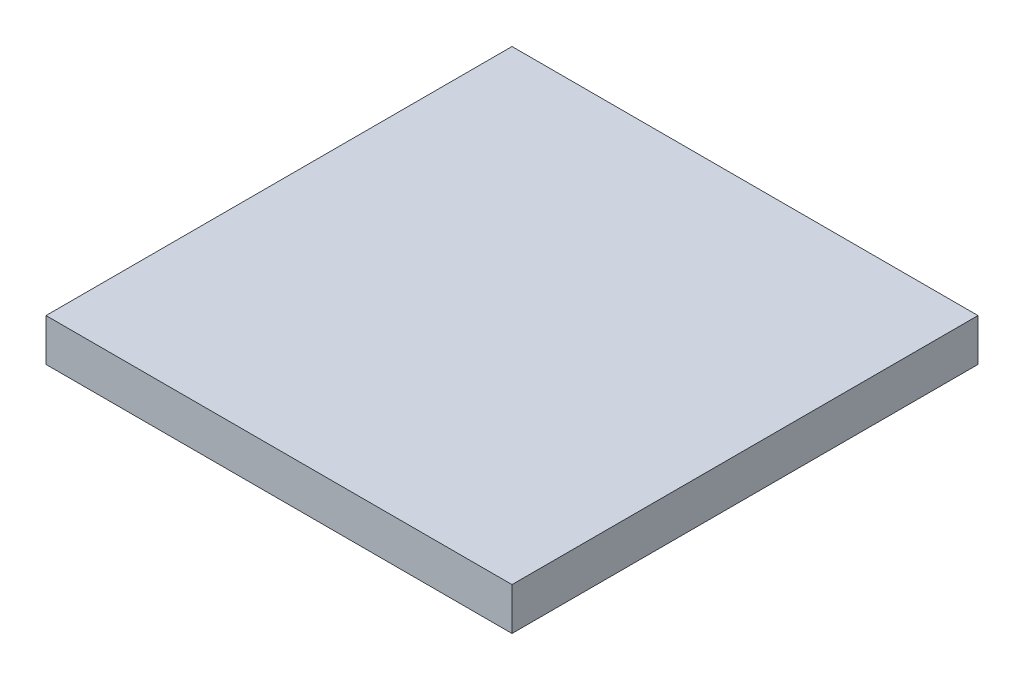
SolidWorks part; units mm, degrees
ref_plane "Front Plane" through (0, 0, 0) normal (0, 0, 1) x (1, 0, 0)
ref_plane "Top Plane" through (0, 0, 0) normal (0, 1, 0) x (1, 0, 0)
ref_plane "Right Plane" through (0, 0, 0) normal (1, 0, 0) x (0, 0, -1)
sketch "Sketch1" plane through (0, 0, 0) normal (0, 1, 0) x (1, 0, 0)
  line L1 (-11, 11) -> (11, 11)
  line L2 (-11, 11) -> (-11, -11)
  line L3 (-11, -11) -> (11, -11)
  line L4 (11, 11) -> (11, -11)
  line L5 (-11, 11) -> (11, -11) construction
  line L6 (-11, -11) -> (11, 11) construction
  point P0 (0, 0)
  dimension "D1" = 22
extrude "Boss-Extrude1" add sketch "Sketch1" along normal mid plane 2
sketch "Sketch2" plane through (0, -1, 0) normal (0, -1, 0) x (1, 0, 0)
  line L1 (8.75, -8.75) -> (0, -8.75) construction
  line L2 (8.75, -8.75) -> (8.75, 8.75) construction
  line L4 (-8.75, -8.75) -> (-8.75, 8.75) construction
  line L5 (8.75, -8.75) -> (-8.75, 8.75) construction
  line L6 (8.75, 8.75) -> (-8.75, -8.75) construction
  line L7 (0, -7.5784) -> (7.25, -7.5784) construction
  line L8 (-7.5784, -7.5784) -> (-7.5784, 7.9216) construction
  line L10 (7.25, -7.5784) -> (7.25, 7.25) construction
  line L11 (-7.5784, -7.5784) -> (7.25, 7.25) construction
  line L12 (-7.5784, 7.9216) -> (7.25, -7.5784) construction
  line L13 (0, 11.6827) -> (0, -12.9744) construction
  line L15 (-7.25, 7.25) -> (-7.25, 8.75)
  line L16 (-8.75, -8.75) -> (8.75, -8.75)
  line L17 (-8.75, -8.75) -> (-8.75, 8.75)
  line L18 (-8.75, 8.75) -> (-7.25, 8.75)
  line L19 (0, -8.75) -> (-8.75, -8.75) construction
  line L20 (-7.5784, -7.5784) -> (0, -7.5784) construction
  line L21 (-6.8004, 0) -> (6.0801, 0) construction
  line L26 (8.75, -8.75) -> (8.75, 8.75)
  line L27 (-8.75, -8.75) -> (8.75, 8.75) construction
  line L28 (-8.75, 8.75) -> (8.75, -8.75) construction
  line L29 (-7.25, -7.25) -> (7.25, -7.25)
  line L30 (-7.25, -7.25) -> (-7.25, 7.25)
  line L31 (0, 7.25) -> (7.25, 7.25) construction
  line L32 (7.25, -7.25) -> (7.25, 7.25)
  line L33 (-7.25, -7.25) -> (7.25, 7.25) construction
  line L34 (-7.25, 7.25) -> (7.25, -7.25) construction
  line L35 (7.25, 7.25) -> (7.25, 8.75)
  line L36 (-7.25, 7.25) -> (0, 7.25) construction
  line L37 (-7.25, 8.75) -> (0, 8.75) construction
  line L38 (7.25, 8.75) -> (8.75, 8.75)
  line L39 (0, 8.75) -> (7.25, 8.75) construction
  point P0 (0, 0)
  point P5 (0, 0)
  point P11 (0, 0)
  point P12 (0, 0)
  dimension "D1" = 17.5
  dimension "D2" = 15.5
  dimension "D3" = 1.5
extrude "Boss-Extrude2" add sketch "Sketch2" along normal blind 2
